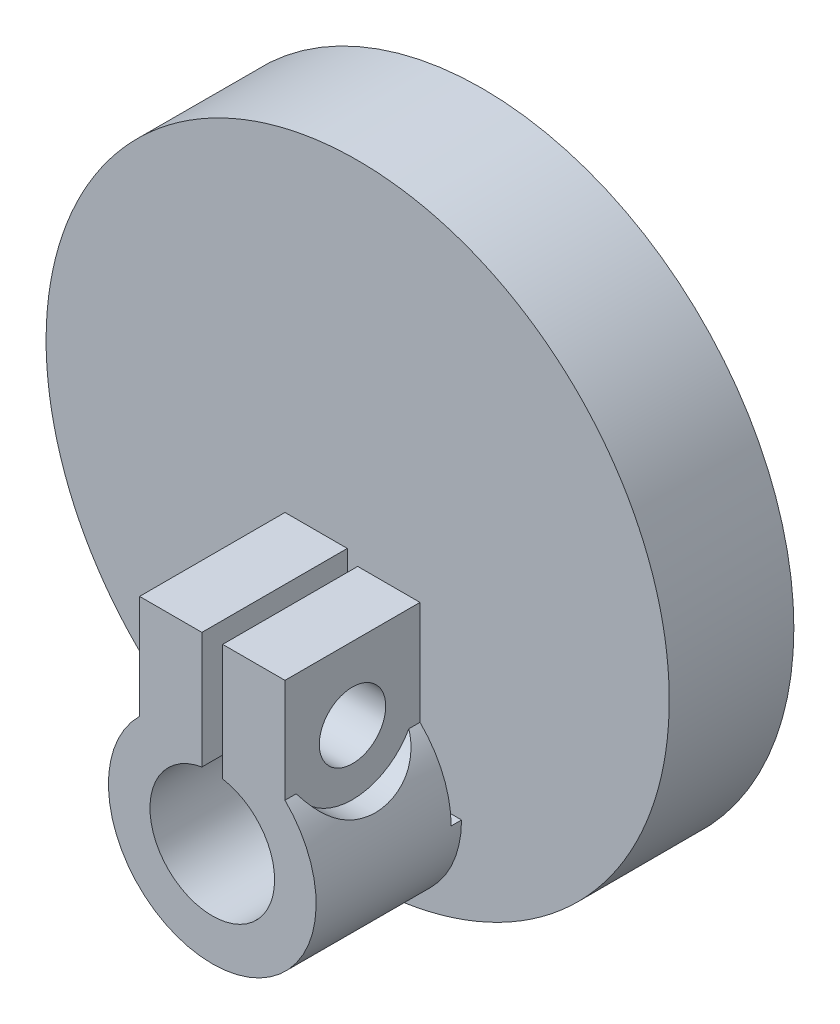
SolidWorks part; units mm, degrees
ref_plane "Front Plane" through (0, 0, 0) normal (0, 0, 1) x (1, 0, 0)
ref_plane "Top Plane" through (0, 0, 0) normal (0, 1, 0) x (1, 0, 0)
ref_plane "Right Plane" through (0, 0, 0) normal (1, 0, 0) x (0, 0, -1)
sketch "Sketch2" plane through (0, 0, 0) normal (0, 0, 1) x (1, 0, 0)
  line L0 (0, -15) -> (50000, -15) construction
  line L1 (0, -7) -> (50000, -7) construction
  line L2 (0, -13) -> (50000, -13) construction
  circle A0 centre (0, 0) radius 15
  circle A1 centre (0, -10) radius 3
  dimension "D2" = 6
  dimension "D4" = 30
  dimension "D3" = 7
  dimension "D1" = 2
extrude "Boss-Extrude1" add sketch "Sketch2" along normal blind 6
sketch "Sketch3" plane through (0, 0, 6) normal (0, 0, 1) x (1, 0, 0)
  line L0 (0.5, -7.042) -> (0.5, -1.4293)
  line L1 (0.5, -1.4293) -> (3.5, -1.4293)
  line L2 (3.5, -1.4293) -> (3.5, -6.4293)
  line L3 (-0.5, -7.042) -> (-0.5, -1.4293)
  line L4 (-0.5, -1.4293) -> (-3.5, -1.4293)
  line L5 (-3.5, -1.4293) -> (-3.5, -6.4293)
  line L6 (-0.5, -1.4293) -> (0.5, -1.4293) construction
  line L7 (-3.5, -5) -> (3.5, -5) construction
  arc A2 (-3.5, -6.4293) -> (3.5, -6.4293) centre (0, -10) ccw
  circle A3 centre (0, -10) radius 3 construction
  arc A4 (-0.5, -7.042) -> (0.5, -7.042) centre (0, -10) ccw
  circle A5 centre (0, 0) radius 15 construction
  point P1 (0, 0)
  point P3 (0, 0)
  point P14 (0, 0)
  point P19 (0, -1.4293)
  dimension "D1" = 1
  dimension "D2" = 3
  dimension "D3" = 5
  dimension "D4" = 5
extrude "Boss-Extrude2" add sketch "Sketch3" along normal blind 7
sketch "Sketch4" plane through (3.5, 0, 0) normal (1, 0, 0) x (0, 0, -1)
  line L1 (-6, -1.4293) -> (-6.5, -1.4293)
  line L2 (-6, -1.4293) -> (-6, -10)
  line L3 (-6, -10) -> (-6.5, -10)
  line L4 (-6.5, -1.4293) -> (-6.5, -10)
  dimension "D1" = 0.5
  dimension "D2" = 5
extrude "Cut-Extrude1" cut sketch "Sketch4" against normal up to surface and the other way through all up to face at (-0.5, -4.2356, 9.5)
sketch "Sketch5" plane through (3.5, 0, 0) normal (1, 0, 0) x (0, 0, -1)
  line L0 (-13, -1.4293) -> (-6.5, -1.4293) construction
  circle A0 centre (-9.75, -4.9293) radius 1.6
  point P2 (-9.75, -1.4293)
  point P3 (0, 0)
  dimension "D1" = 3.2
  dimension "D2" = 3.5
extrude "Cut-Extrude2" cut sketch "Sketch5" against normal through all
sketch "Sketch6" plane through (3.5, 0, 0) normal (1, 0, 0) x (0, 0, -1)
  circle A0 centre (-9.75, -4.9293) radius 3.1
  dimension "D1" = 6.2
extrude "Cut-Extrude3" cut sketch "Sketch6" along normal through all
sketch "Sketch7" plane through (-3.5, 0, 0) normal (-1, 0, 0) x (0, 0, 1)
  circle A0 centre (9.75, -4.9293) radius 3.1
  dimension "D1" = 6.2
extrude "Cut-Extrude4" cut sketch "Sketch7" along normal through all contours A0
equation "\"translationDistance\"= 7"
equation "\"D3@Sketch2\"=\"translationDistance\""
